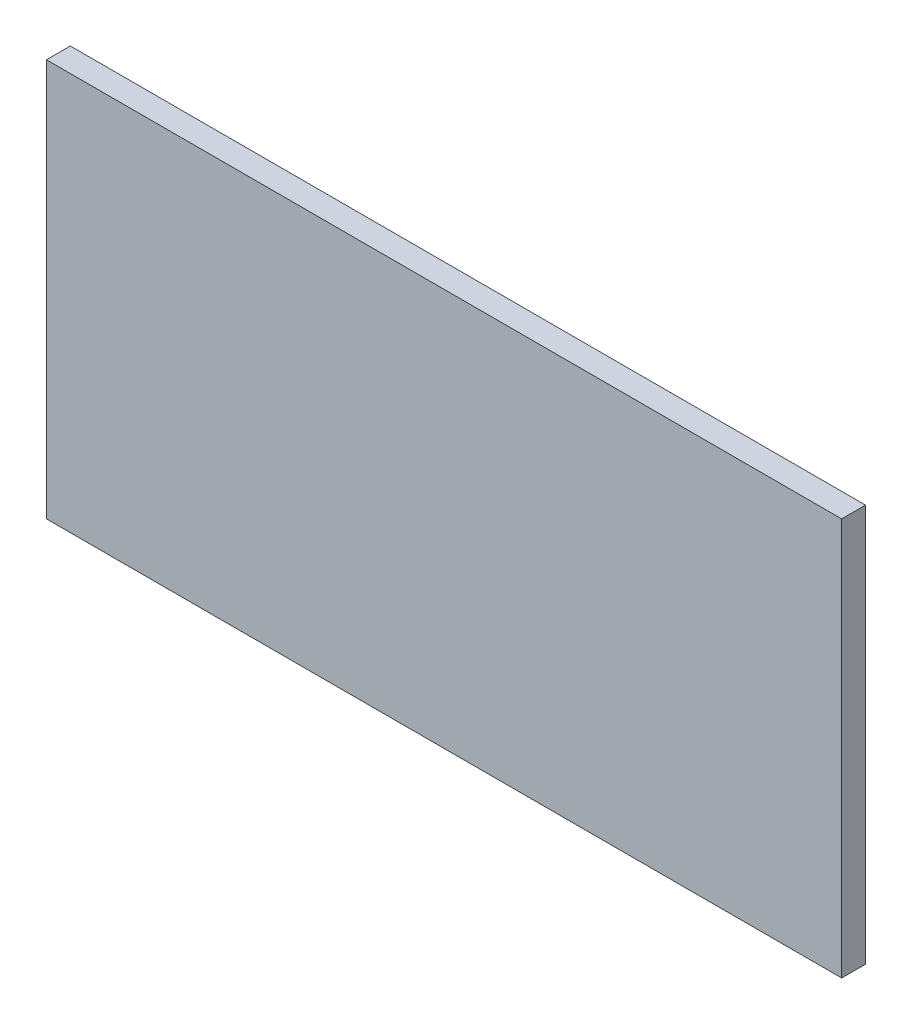
SolidWorks part; units mm, degrees
ref_plane "Plano frontal" through (0, 0, 0) normal (0, 0, 1) x (1, 0, 0)
ref_plane "Plano superior" through (0, 0, 0) normal (0, 1, 0) x (1, 0, 0)
ref_plane "Plano direito" through (0, 0, 0) normal (1, 0, 0) x (0, 0, -1)
sketch "Esboço2" plane through (0, 0, 0) normal (0, 0, 1) x (1, 0, 0)
  line L1 (0, 0) -> (200, 0)
  line L2 (0, 0) -> (0, 100)
  line L3 (0, 100) -> (200, 100)
  line L4 (200, 0) -> (200, 100)
  dimension "D1" = 100
  dimension "D2" = 200
extrude "Ressalto-extrusão1" add sketch "Esboço2" along normal blind 6 contours L3 L4 L1 L2
